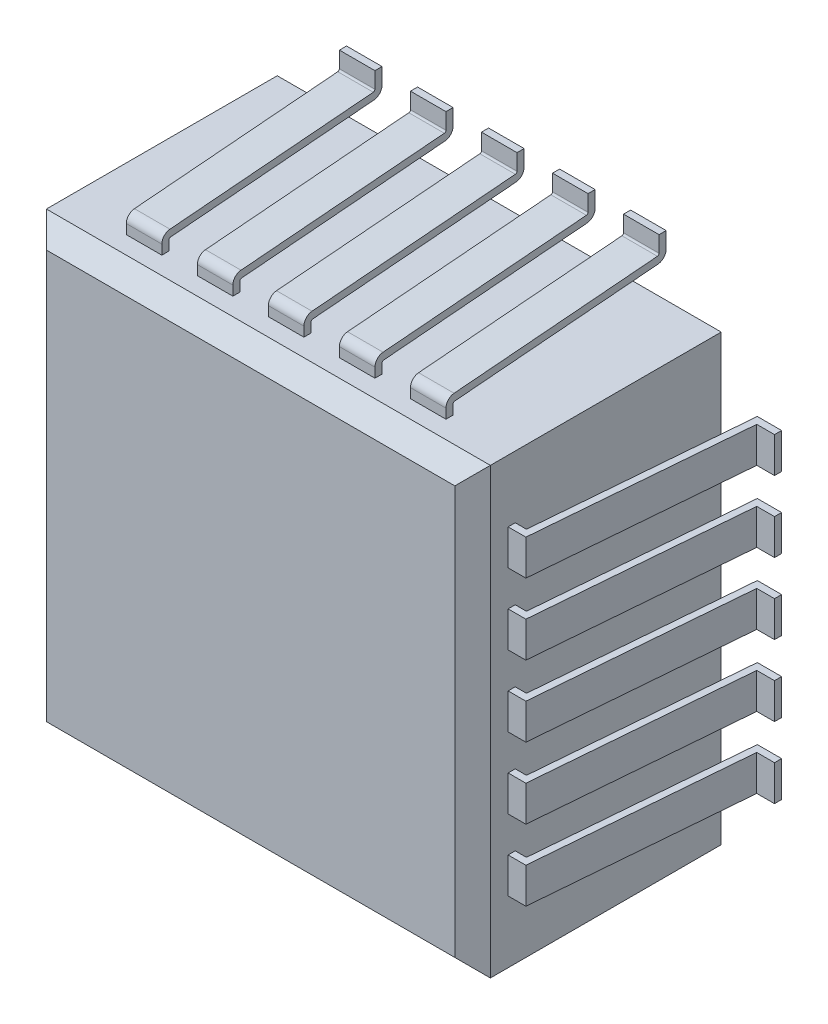
SolidWorks part; units mm, degrees
ref_plane "Front" through (0, 0, 0) normal (0, 0, 1) x (1, 0, 0)
ref_plane "Top" through (0, 0, 0) normal (0, 1, 0) x (1, 0, 0)
ref_plane "Right" through (0, 0, 0) normal (1, 0, 0) x (0, 0, -1)
sketch "COMPONENT_OUTLINE" plane through (0, 0, 0) normal (0, 0, 1) x (1, 0, 0)
  line L0 (-1.25, 1.25) -> (-1.25, -1.25)
  line L1 (-1.25, -1.25) -> (1.25, -1.25)
  line L2 (1.25, -1.25) -> (1.25, 1.25)
  line L3 (1.25, 1.25) -> (-1.25, 1.25)
  line L4 (-1.25, 1.25) -> (1.25, -1.25) construction
  line L5 (-1.25, -1.25) -> (1.25, 1.25) construction
  dimension "D1" = 2.5
  dimension "D2" = 2.5
extrude "Extrude1" add sketch "COMPONENT_OUTLINE" along normal blind 1.4
sketch "Sketch1" plane through (0, 0, 0) normal (1, 0, 0) x (0, 0, -1)
  line L0 (-1.2, 1.25) -> (-1.2, 1.35)
  line L1 (-1.4, 1.25) -> (0, 1.25) construction
  line L2 (-1.2, 1.35) -> (0, 1.45)
  line L3 (0, 1.45) -> (0, 1.55)
  dimension "D1" = 0.1
  dimension "D2" = 0.2
  dimension "D3" = 0.2
  dimension "D4" = 0.1
extrude "Extrude-Thin1" add sketch "Sketch1" along normal mid plane 0.2 thin
pattern_linear "LPattern1" count 3 spacing 0.4 along (-1, 0, 0) count 3 spacing 0.4 along (1, 0, 0) of "Extrude-Thin1"
mirror "Mirror1" about plane through (0, 0, 0) normal (0, 1, 0) of "Extrude-Thin1", "LPattern1"
sketch "Sketch2" plane through (0, 0, 0) normal (0, 1, 0) x (1, 0, 0)
  line L0 (1.25, -1.2) -> (1.35, -1.2)
  line L1 (1.25, -1.4) -> (1.25, 0) construction
  line L2 (1.35, -1.2) -> (1.45, 0)
  line L3 (1.45, 0) -> (1.55, 0)
  line L4 (1.25, -1.4) -> (-1.25, -1.4) construction
  dimension "D1" = 0.1
  dimension "D2" = 0.2
  dimension "D3" = 0.2
  dimension "D4" = 0.1
extrude "Extrude-Thin2" add sketch "Sketch2" along normal mid plane 0.2 thin thin type one direction reverse wall 0.04
pattern_linear "LPattern2" count 3 spacing 0.4 along (0, 1, 0) count 3 spacing 0.4 along (0, -1, 0) of "Extrude-Thin2"
mirror "Mirror2" about plane through (0, 0, 0) normal (1, 0, 0) of "LPattern2", "Extrude-Thin2"
chamfer "Chamfer1" distance 0.1 angle 45 4 edges at (1.25, 0, 1.4) (0, -1.25, 1.4) (-1.25, 0, 1.4) (0, 1.25, 1.4)
